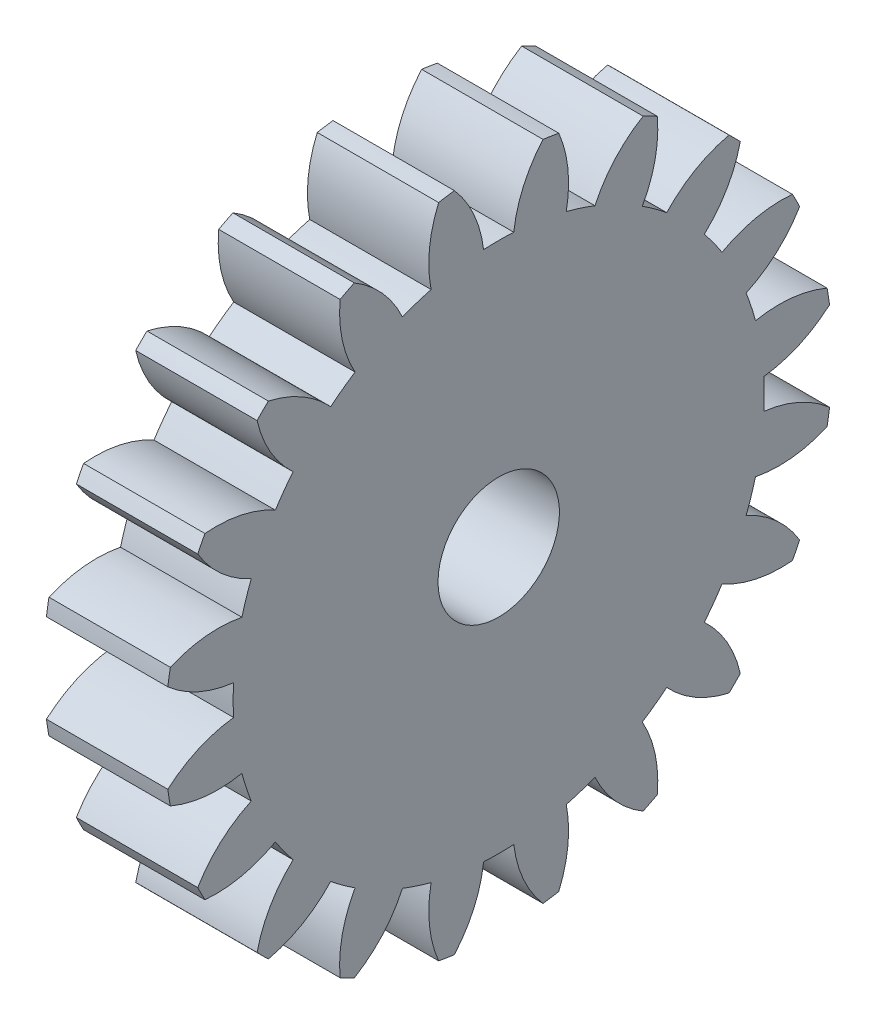
SolidWorks part; units mm, degrees
ref_plane "Plane1" through (0, 0, 0) normal (0, 0, 1) x (1, 0, 0)
ref_plane "Plane2" through (0, 0, 0) normal (0, 1, 0) x (1, 0, 0)
ref_plane "Plane3" through (0, 0, 0) normal (1, 0, 0) x (0, 0, -1)
other "Configuration Table"
sketch "HoldingSke" plane through (0, 0, 0) normal (0, 1, 0) x (1, 0, 0)
  line L0 (0, 0) -> (190.9455, -69.4985)
  line L1 (-15, 0) -> (100, 0) construction
  line L2 (0, 0) -> (-2.1039, 2.3779)
  line L3 (0, 0) -> (-11.863, 4.5341)
  line L4 (0, 0) -> (8.1152, 2.9537)
  line L5 (0, 0) -> (-47.5972, -17.7524)
  line L6 (0, 0) -> (-10.5278, -7.1032)
  line L7 (-2.1039, 2.3779) -> (8.8308, 51.9871)
  line L8 (-76.2, 54.61) -> (-61.976, 54.61)
  line L9 (-71.009, 38.7566) -> (-53.1078, 45.2721)
  line L10 (-76.2, 71.12) -> (104.1128, 71.12)
  line L11 (0, 0) -> (-12.7, 0)
  line L12 (-76.2, 101.6) -> (-76.0857, 101.6)
  line L13 (24.9733, 27.94) -> (52.9518, 28.4284)
  line L14 (24.9733, 27.94) -> (24.9746, 27.94)
  line L15 (24.9733, 27.94) -> (100.4006, 29.5858)
  circle A0 centre (0, 0) radius 6.35
  circle A1 centre (0, 0) radius 27.78
  circle A2 centre (0, 0) radius 38.1
  circle A3 centre (0, 0) radius 6.35
  dimension "MHD" = 55.56
  dimension "Hub_dia" = 76.2
  dimension "Bore" = 12.7
  dimension "MBD" = 12.7
  dimension "Num_teeth" = 20
  dimension "Pitch" = 203.2
  dimension "Overall_len" = 50.8
  dimension "Show_teeth" = 20
  dimension "Thickness" = 12.7
  dimension "OAL" = 50.8001
  dimension "T_dim" = 14.224
  dimension "Ap" = 20
  dimension "H" = 19.05
  dimension "Pitch_radius" = 180.3128
  dimension "Width" = 12.7
  dimension "Backlash" = 0.1143
  dimension "Addendum_fac" = 1
  dimension "Dedendum_fac" = 1.25
  dimension "Clearance_fac" = 0.25
  dimension "Dedendum_add" = 0.0013
sketch "BasProSke" plane through (0, 0, 0) normal (0, 1, 0) x (1, 0, 0)
  line L0 (-10, 0) -> (60, 0) construction
  line L1 (0, 0) -> (0, 34.925)
  line L2 (0, 0) -> (12.7, 0)
  line L3 (12.7, 0) -> (12.7, 34.925)
  line L4 (12.7, 34.925) -> (0, 34.925)
  dimension "Thickness" = 12.7
  dimension "Diameter" = 69.85
revolve "Base-Revolve" add sketch "BasProSke" angle 360 about L0
sketch "TooCutSke" plane through (0, 0, 0) normal (1, 0, 0) x (0, 0, -1)
  line L1 (0, 0) -> (0, 107) construction
  line L2 (0, 0) -> (-2.691, 31.6358) construction
  line L3 (0, 0) -> (-9.9077, 62.5547) construction
  line L4 (-2.691, 31.6358) -> (-4.9538, 31.2774) construction
  arc A0 (1.5778, 27.7351) -> (-1.5778, 27.7351) centre (0, 0) ccw
  arc A1 (4.6592, 34.6384) -> (-4.6592, 34.6384) centre (0, 0) ccw
  circle A2 centre (0, 0) radius 31.75 construction
  circle A3 centre (0, 0) radius 29.8352 construction
  arc A4 (-1.5778, 27.7351) -> (-4.6592, 34.6384) centre (-14.19, 26.2447) ccw
  arc A5 (4.6592, 34.6384) -> (1.5778, 27.7351) centre (14.19, 26.2447) ccw
  dimension "Root_dia" = 55.56
  dimension "Overcut_dia" = 69.9008
  dimension "Pitch_dia" = 63.5
  dimension "Base_dia" = 59.6705
  dimension "Flank_rad" = 12.7
  dimension "Half_ang" = 9
  dimension "Half_CT" = 2.2911
extrude "ToothCut" cut sketch "TooCutSke" along normal through all
fillet "Breaks" [suppressed] radius 0.0635
fillet "RootFillets" [suppressed] radius 0.795
pattern_circular "TeethCuts" count 20 every 18 about axis through (-10, 0, 0) along (1, 0, 0) of "ToothCut", "RootFillets", "Breaks"
sketch "HubNeaOneSke" plane through (0, 0, 0) normal (-1, 0, 0) x (0, 0, 1)
  circle A0 centre (0, 0) radius 27.78
  dimension "Diameter" = 55.56
extrude "HubNearOne" [suppressed] add sketch "HubNeaOneSke" along normal blind 38.1001
sketch "HubNeaBotSke" plane through (0, 0, 0) normal (-1, 0, 0) x (0, 0, 1)
  circle A0 centre (0, 0) radius 27.78
  dimension "Diameter" = 55.56
extrude "HubNearBoth" [suppressed] add sketch "HubNeaBotSke" along normal blind 19.05
ref_plane "FarPln" through (12.7, 0, 0) normal (1, 0, 0) x (0, 0, -1)
sketch "HubFarSke" plane through (12.7, 0, 0) normal (1, 0, 0) x (0, 0, -1)
  circle A0 centre (0, 0) radius 27.78
  dimension "Diameter" = 55.56
extrude "HubFar" [suppressed] add sketch "HubFarSke" along normal blind 19.05
sketch "BorSke" plane through (0, 0, 0) normal (1, 0, 0) x (0, 0, -1)
  circle A0 centre (0, 0) radius 6.35
  dimension "Diameter" = 12.7
extrude "Bore" cut sketch "BorSke" along normal mid plane 101.6001
sketch "KeySke" plane through (0, 0, 0) normal (1, 0, 0) x (0, 0, -1)
  line L0 (-1.5875, 0) -> (-1.5875, 7.874)
  line L1 (-1.5875, 7.874) -> (1.5875, 7.874)
  line L2 (1.5875, 7.874) -> (1.5875, 0)
  line L3 (0, 0) -> (0, 34) construction
  line L4 (-1.5875, 0) -> (1.5875, 0)
  dimension "Offset" = 7.874
  dimension "Width" = 3.175
extrude "Keyway" [suppressed] cut sketch "KeySke" along normal mid plane 101.6001
pattern_circular "Keyway2" [suppressed] count 2 every 90 about axis through (-10, 0, 0) along (1, 0, 0)
equation "' \"Pitch@HoldingSke\" = 4"
equation "' \"Num_teeth@HoldingSke\" = 12"
equation "' \"Ap@HoldingSke\" =  20"
equation "' \"Ap@HoldingSke\" = 20"
equation "' \"Width@HoldingSke\" = 0.5"
equation "' \"Hub_dia@HoldingSke\"= 1"
equation "' \"Hub_dia@HoldingSke\" = 1"
equation "' \"Overall_len@HoldingSke\" = 1.0"
equation "' \"Bore@HoldingSke\" = 0.75"
equation "' \"T_dim@HoldingSke\" = 0.85"
equation "' \"Width@KeySke\" = 0.25"
equation "' \"Show_teeth@HoldingSke\" = 13"
equation "' \"Backlash@HoldingSke\" = 0.009"
equation "' \"Addendum_fac@HoldingSke\" = 1.0"
equation "' \"Dedendum_fac@HoldingSke\" = 1.25"
equation "' \"Dedendum_add@HoldingSke\" = 0.00005"
equation "' \"Clearance_fac@HoldingSke\" = 0.25"
equation "' \"Pitch@HoldingSke\" = 0.5"
equation "' \"Num_teeth@HoldingSke\" = 23"
equation "' \"Show_teeth@HoldingSke\" = 23"
equation "' \"Backlash@HoldingSke\" = 0.0375"
equation "\"Overcut_dia@TooCutSke\" = (\"Num_teeth@HoldingSke\" + 2 * \"Addendum_fac@HoldingSke\") / \"Pitch@HoldingSke\" + 0.002"
equation "\"Pitch_dia@TooCutSke\" = \"Num_teeth@HoldingSke\" / \"Pitch@HoldingSke\""
equation "\"Base_dia@TooCutSke\" = \"Num_teeth@HoldingSke\" / \"Pitch@HoldingSke\" * cos((\"Ap@HoldingSke\"  * 3.14159265 / 180))"
equation "\"Root_dia@TooCutSke\" = (\"Num_teeth@HoldingSke\" + 2) / \"Pitch@HoldingSke\" - 2 * (\"Addendum_fac@HoldingSke\" + \"Dedendum_fac@HoldingSke\") / \"Pitch@HoldingSke\" - \"Dedendum_add@HoldingSke\" * 2"
equation "\"Half_ang@TooCutSke\" = 180 / \"Num_teeth@HoldingSke\""
equation "\"Half_CT@TooCutSke\" = \"Num_teeth@HoldingSke\" / \"Pitch@HoldingSke\" * sin((3.14159265 / 2 / \"Num_teeth@HoldingSke\")) / 2 - 7 * \"Backlash@HoldingSke\" / 4"
equation "\"Flank_rad@TooCutSke\" = \"Num_teeth@HoldingSke\" / \"Pitch@HoldingSke\" / 5"
equation "\"Radius@RootFillets\" = \"Clearance_fac@HoldingSke\" / \"Pitch@HoldingSke\" + \"Dedendum_add@HoldingSke\""
equation "\"Break_rad@Breaks\" = 0.02 / \"Pitch@HoldingSke\""
equation "\"Thickness@HoldingSke\" = \"Width@HoldingSke\""
equation "\"OAL@HoldingSke\" = \"Thickness@HoldingSke\""
equation "\"MHD@HoldingSke\" = (\"Num_teeth@HoldingSke\" + 2) / \"Pitch@HoldingSke\" - 2 * (\"Addendum_fac@HoldingSke\" + \"Dedendum_fac@HoldingSke\")  / \"Pitch@HoldingSke\" - \"Dedendum_add@HoldingSke\" * 2"
equation "\"MBD@HoldingSke\" = (\"Num_teeth@HoldingSke\" + 2) / \"Pitch@HoldingSke\" - 2 * (\"Addendum_fac@HoldingSke\" + \"Dedendum_fac@HoldingSke\")  / \"Pitch@HoldingSke\" - \"Dedendum_add@HoldingSke\" * 2 - 0.002"
equation "\"MHD@HoldingSke\" = ((sgn( \"MHD@HoldingSke\" - \"Hub_dia@HoldingSke\" )-1)*( \"MHD@HoldingSke\" - \"Hub_dia@HoldingSke\" ))/-2+ \"Hub_dia@HoldingSke\""
equation "\"MBD@HoldingSke\" = ((sgn( \"MBD@HoldingSke\" - \"Bore@HoldingSke\" )-1)*( \"MBD@HoldingSke\" - \"Bore@HoldingSke\" ))/-2+ \"Bore@HoldingSke\""
equation "\"OAL@HoldingSke\" = ((sgn( \"OAL@HoldingSke\" - \"Overall_len@HoldingSke\" )+1)*( \"OAL@HoldingSke\" - \"Overall_len@HoldingSke\" ))/2 + \"Overall_len@HoldingSke\" + 0.000002"
equation "\"Num_teeth@TeethCuts\" = int( \"Show_teeth@HoldingSke\" ) + 1"
equation "\"Num_teeth@TeethCuts\" = ((sgn( \"Num_teeth@TeethCuts\" - \"Num_teeth@HoldingSke\" )-1)*( \"Num_teeth@TeethCuts\" - \"Num_teeth@HoldingSke\" ))/-2+ \"Num_teeth@HoldingSke\""
equation "\"Num_teeth@TeethCuts\" = ((sgn( \"Num_teeth@TeethCuts\" - 2.0)+1)*( \"Num_teeth@TeethCuts\" - 2.0))/2 +2.0"
equation "\"Angle@TeethCuts\" = 360.0 / \"Num_teeth@HoldingSke\""
equation "\"Diameter@BasProSke\" = (\"Num_teeth@HoldingSke\" + 2 * \"Addendum_fac@HoldingSke\") / \"Pitch@HoldingSke\""
equation "\"Thickness@BasProSke\"  = \"Thickness@HoldingSke\""
equation "' \"Fillet_rad@BasProSke\" =  \"Thickness@HoldingSke\" * 0.05"
equation "' \"Fillet_rad@BasProSke\" = \"Thickness@HoldingSke\" * 0.05"
equation "\"MHD@HoldingSke\" = ((sgn( \"MHD@HoldingSke\" - \"Root_dia@TooCutSke\" )-1)*( \"MHD@HoldingSke\" - \"Root_dia@TooCutSke\" ))/-2+ \"Root_dia@TooCutSke\""
equation "\"Diameter@HubNeaOneSke\" = \"MHD@HoldingSke\""
equation "\"Length@HubNearOne\" = \"OAL@HoldingSke\" - \"Thickness@BasProSke\""
equation "\"Diameter@HubNeaBotSke\" = \"MHD@HoldingSke\""
equation "\"Length@HubNearBoth\" = ( \"OAL@HoldingSke\" - \"Thickness@BasProSke\" ) / 2.0"
equation "\"Thickness@FarPln\" = \"Thickness@BasProSke\""
equation "\"Diameter@HubFarSke\" = \"MHD@HoldingSke\""
equation "\"Length@HubFar\" = ( \"OAL@HoldingSke\" - \"Thickness@BasProSke\" ) / 2.0"
equation "\"Diameter@BorSke\" = \"MBD@HoldingSke\""
equation "\"D1@Bore\" = \"OAL@HoldingSke\" * 2.0"
equation "\"D1@Keyway\" = \"OAL@HoldingSke\" * 2.0"
equation "\"Offset@KeySke\" = \"T_dim@HoldingSke\" - \"MBD@HoldingSke\" / 2.0"
